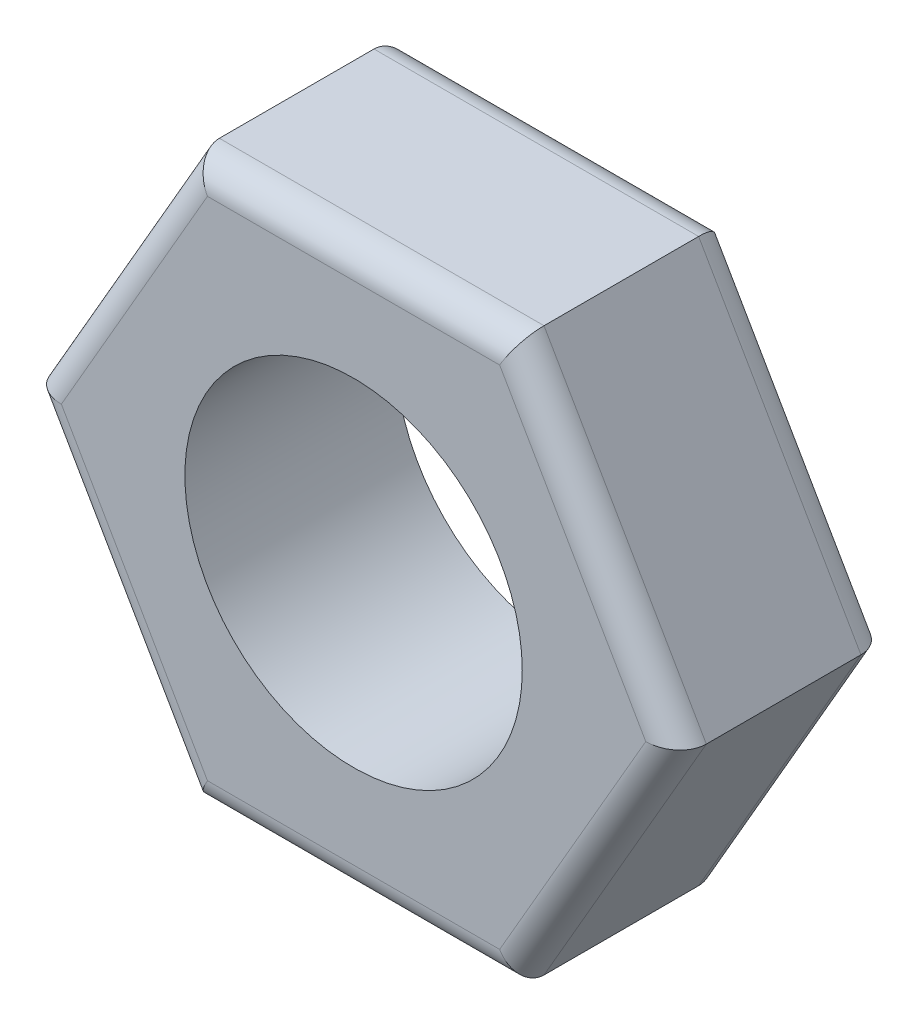
SolidWorks part; units mm, degrees
ref_plane "前视基准面" through (0, 0, 0) normal (0, 0, 1) x (1, 0, 0)
ref_plane "上视基准面" through (0, 0, 0) normal (0, 1, 0) x (1, 0, 0)
ref_plane "右视基准面" through (0, 0, 0) normal (1, 0, 0) x (0, 0, -1)
sketch "草图1" plane through (0, 0, 0) normal (0, 0, 1) x (1, 0, 0)
  line L1 (5.7735, -10) -> (11.547, 0)
  line L2 (11.547, 0) -> (5.7735, 10)
  line L3 (5.7735, 10) -> (-5.7735, 10)
  line L4 (-5.7735, 10) -> (-11.547, 0)
  line L5 (-11.547, 0) -> (-5.7735, -10)
  line L6 (-5.7735, -10) -> (5.7735, -10)
  circle A0 centre (0, 0) radius 10 construction
  dimension "D1" = 20
extrude "凸台-拉伸3" add sketch "草图1" along normal blind 7.5
fillet "圆角3" radius 1 12 edges at (8.6603, 5, 0) (8.6603, -5, 0) (0, -10, 0) (-8.6603, -5, 0) (-8.6603, 5, 0) (0, 10, 0) (-8.6603, 5, 7.5) (-8.6603, -5, 7.5) (0, -10, 7.5) (8.6603, -5, 7.5) (8.6603, 5, 7.5) (0, 10, 7.5)
sketch "草图4" plane through (0, 0, 7.5) normal (0, 0, 1) x (1, 0, 0)
  circle A0 centre (0, 0) radius 6
  dimension "D1" = 12
extrude "切除-拉伸1" cut sketch "草图4" against normal through all
